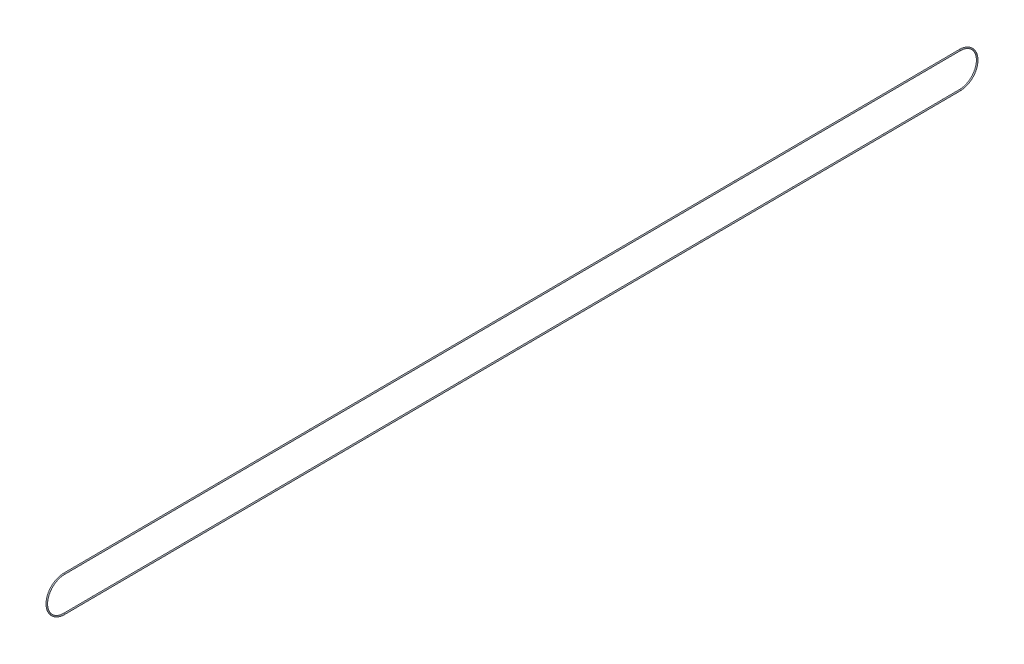
SolidWorks part; units mm, degrees
ref_plane "Front Plane" through (0, 0, 0) normal (0, 0, 1) x (1, 0, 0)
ref_plane "Top Plane" through (0, 0, 0) normal (0, 1, 0) x (1, 0, 0)
ref_plane "Right Plane" through (0, 0, 0) normal (1, 0, 0) x (0, 0, -1)
sketch "Sketch1" plane through (0, 0, 0) normal (1, 0, 0) x (0, 0, -1)
  line L0 (-580, -3.6943) -> (580, 3.6943) construction
  line L1 (-580.1433, 18.8053) -> (579.8567, 26.1938)
  line L2 (-579.8567, -26.1938) -> (580.1433, -18.8053)
  arc A0 (-580.1433, 18.8053) -> (-579.8567, -26.1938) centre (-580, -3.6943) ccw
  arc A1 (580.1433, -18.8053) -> (579.8567, 26.1938) centre (580, 3.6943) ccw
  point P2 (0, 0)
  point P7 (0, 0)
  dimension "D2" = 45
  dimension "D1" = 1160
sweep "Sweep1" add path "Sketch1" circular profile diameter 1.5 parameters "D3"=1.5
